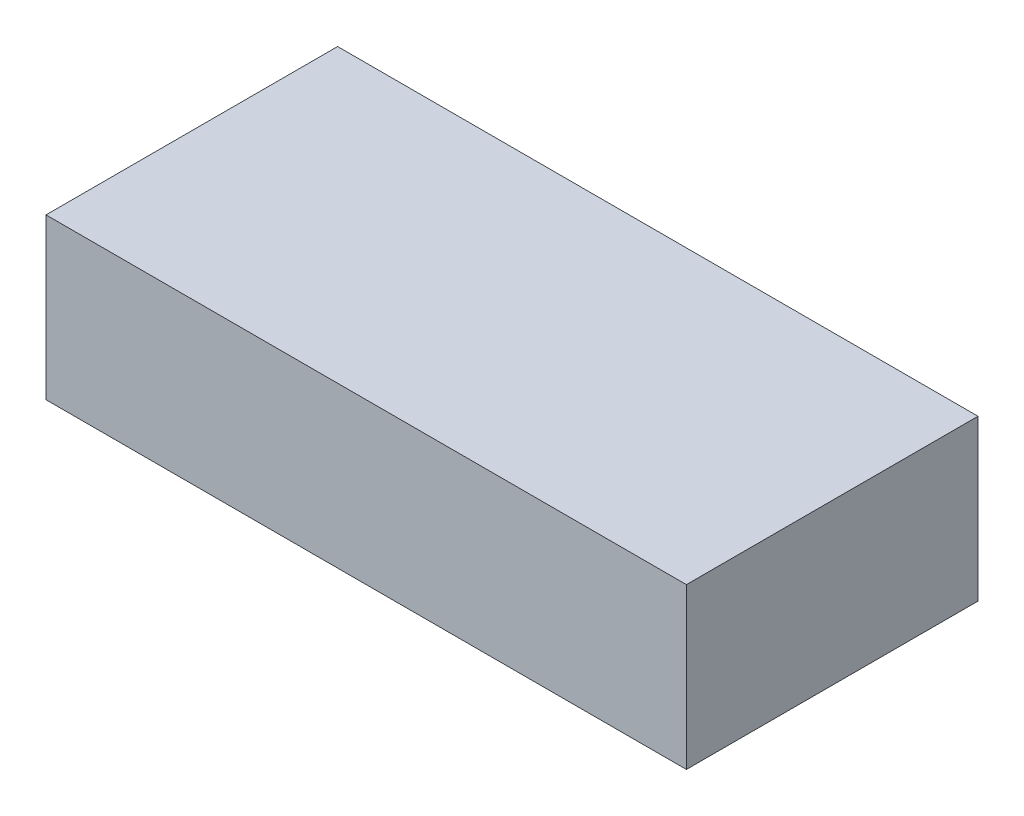
SolidWorks part; units mm, degrees
ref_plane "Front Plane" through (0, 0, 0) normal (0, 0, 1) x (1, 0, 0)
ref_plane "Top Plane" through (0, 0, 0) normal (0, 1, 0) x (1, 0, 0)
ref_plane "Right Plane" through (0, 0, 0) normal (1, 0, 0) x (0, 0, -1)
sketch "Sketch1" plane through (0, 0, 0) normal (0, 1, 0) x (1, 0, 0)
  line L1 (-28, -12.75) -> (28, -12.75)
  line L2 (-28, -12.75) -> (-28, 12.75)
  line L3 (-28, 12.75) -> (28, 12.75)
  line L4 (28, -12.75) -> (28, 12.75)
  line L5 (-28, -12.75) -> (28, 12.75) construction
  line L6 (-28, 12.75) -> (28, -12.75) construction
  point P0 (0, 0)
  dimension "D1" = 56
  dimension "D2" = 25.5
extrude "Boss-Extrude1" add sketch "Sketch1" along normal blind 14
